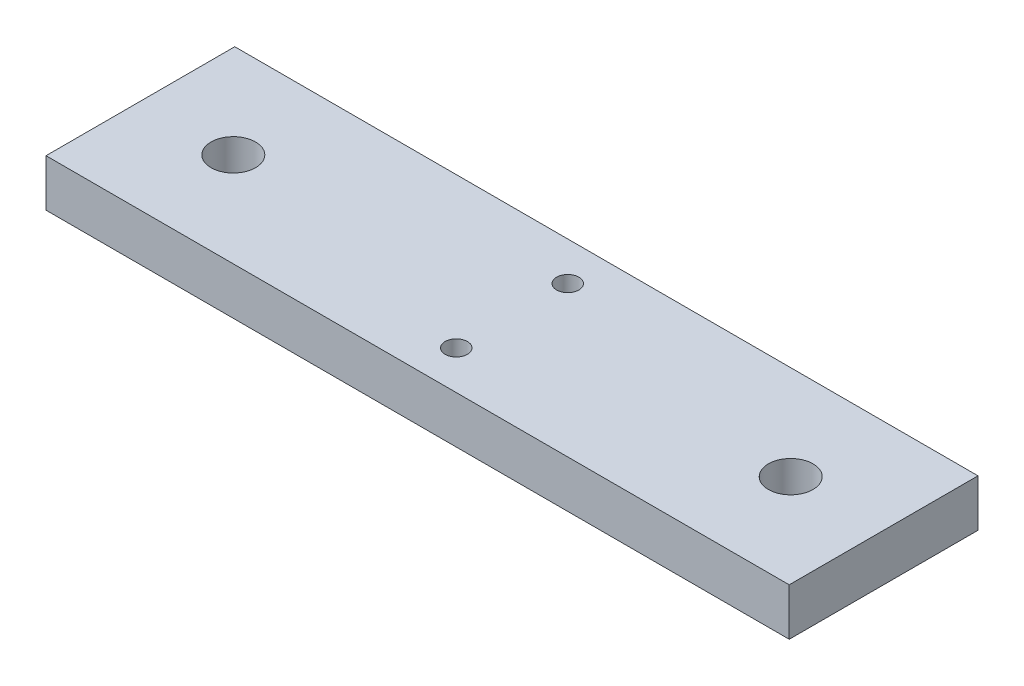
SolidWorks part; units mm, degrees
material "Aleación 1060"
ref_plane "Alzado" through (0, 0, 0) normal (0, 0, 1) x (1, 0, 0)
ref_plane "Planta" through (0, 0, 0) normal (0, 1, 0) x (1, 0, 0)
ref_plane "Vista lateral" through (0, 0, 0) normal (1, 0, 0) x (0, 0, -1)
sketch "Croquis1" plane through (0, 0, 0) normal (0, 1, 0) x (1, 0, 0)
  line L0 (0, -43.7705) -> (0, 43.7705) construction
  line L1 (100, -25.4) -> (-100, -25.4)
  line L2 (100, -25.4) -> (100, 25.4)
  line L3 (100, 25.4) -> (-100, 25.4)
  line L4 (-100, -25.4) -> (-100, 25.4)
  line L5 (100, -25.4) -> (-100, 25.4) construction
  line L6 (100, 25.4) -> (-100, -25.4) construction
  line L7 (-100, 0) -> (100, 0) construction
  circle A0 centre (0, 15) radius 3
  circle A1 centre (0, -15) radius 3
  circle A2 centre (-75, 0) radius 6
  circle A3 centre (75, 0) radius 6
  point P0 (0, 0)
  point P9 (0, 0)
  point P16 (0, 0)
  dimension "D4" = 6
  dimension "D6" = 6
  dimension "D7" = 12
  dimension "D8" = 12
  dimension "D1" = 50.8
  dimension "D2" = 200
  dimension "D3" = 15
  dimension "D5" = 15
  dimension "D9" = 75
  dimension "D10" = 75
extrude "Saliente-Extruir1" add sketch "Croquis1" along normal blind 12.7
equation "\"D5@Croquis1\"=\"D3@Croquis1\""
equation "\"D6@Croquis1\"=\"D4@Croquis1\""
